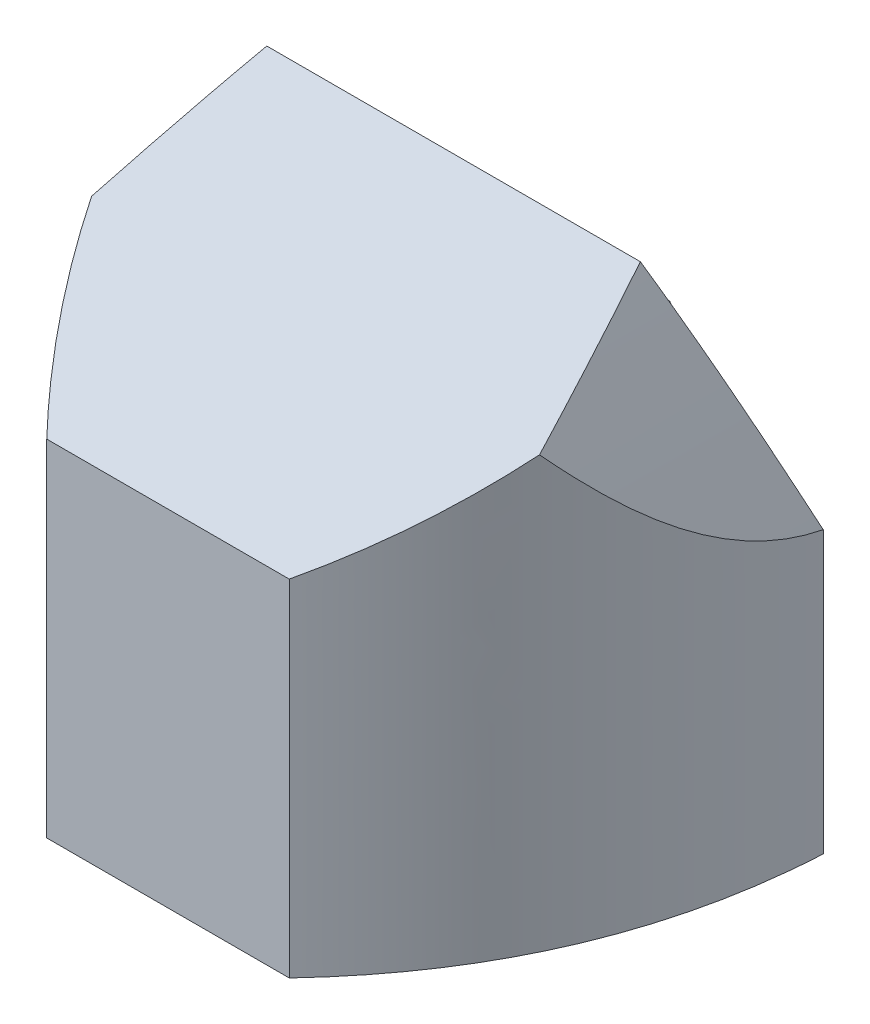
SolidWorks part; units mm, degrees
ref_plane "Front Plane" through (0, 0, 0) normal (0, 0, 1) x (1, 0, 0)
ref_plane "Top Plane" through (0, 0, 0) normal (0, 1, 0) x (1, 0, 0)
ref_plane "Right Plane" through (0, 0, 0) normal (1, 0, 0) x (0, 0, -1)
sketch "Sketch2" plane through (0, 0, 0) normal (1, 0, 0) x (0, 0, -1)
  line L0 (0, 0) -> (0, -750) construction
  line L1 (0, -750) -> (-500, -750)
  line L2 (-500, -750) -> (-500, -288.6751)
  line L3 (-500, -288.6751) -> (-118.677, -68.5182)
  line L4 (-118.677, -68.5182) -> (0, -375)
  line L5 (0, -750) -> (0, -375)
  dimension "D1" = 60
  dimension "D2" = 750
  dimension "D3" = 500
extrude "Boss-Extrude1" add sketch "Sketch2" along normal mid plane 1000
sketch "Sketch3" plane through (0, -750, 0) normal (0, -1, 0) x (1, 0, 0)
  line L2 (0, 500) -> (0, 0) construction
  line L4 (-161.9217, 500) -> (-500, 500)
  line L5 (-500, 500) -> (-500, 0)
  line L6 (-500, 0) -> (500, 0)
  line L7 (500, 0) -> (500, 500)
  line L8 (500, 500) -> (-500, 500)
  line L9 (-500, 500) -> (-500, 0)
  line L11 (500, 0) -> (500, 500)
  line L12 (500, 500) -> (161.9217, 500)
  line L13 (500, 500) -> (-500, 500) construction
  line L14 (500, 0) -> (-500, 0) construction
  line L16 (375, 0) -> (500, 0)
  line L17 (-500, 0) -> (-375, 0)
  spline S0 degree 2 poles (-375, 0) (-359.9342, 289.4316) (-161.9217, 500) knots 0 0 0 1 1 1
  spline S1 degree 2 poles (375, 0) (359.9342, 289.4316) (161.9217, 500) knots 0 0 0 1 1 1
  point P7 (-256.7752, 500)
  point P10 (-256.3318, 500)
  point P11 (-311.7603, 275.3697)
  point P14 (-161.9217, 500)
  dimension "D2" = 750
  dimension "D1" = 0
extrude "Cut-Extrude1" cut sketch "Sketch3" against normal blind 1000
sketch "Sketch4" plane through (0, 0, 0) normal (0, 0, -1) x (-1, 0, 0)
  line L0 (0, 174.7035) -> (0, -750) construction
  line L1 (-375, -750) -> (375, -750) construction
  line L3 (-375, -375) -> (-996.2943, -375)
  line L4 (-996.2943, -375) -> (-996.2943, 371.9099)
  line L5 (-996.2943, 371.9099) -> (846.4896, 371.9099)
  line L6 (846.4896, 371.9099) -> (846.4896, -375)
  line L7 (846.4896, -375) -> (375, -375)
  spline S0 degree 2 poles (-375, -375) (0, 724.4071) (375, -375) knots 0 0 0 1 1 1
extrude "Cut-Extrude2" cut sketch "Sketch4" against normal blind 1000
sketch "Sketch5" plane through (0, -48.8966, 126.2749) normal (0, 0.3611, -0.9325) x (-1, 0, 0)
  line L0 (-249.4412, -21.0413) -> (249.4412, -21.0413) construction
  line L1 (254, -289.5188) -> (-254, -289.5188)
  line L2 (254, -289.5188) -> (254, -86.3188)
  line L3 (254, -86.3188) -> (-254, -86.3188)
  line L4 (-254, -289.5188) -> (-254, -86.3188)
  line L5 (254, -289.5188) -> (-254, -86.3188) construction
  line L6 (254, -86.3188) -> (-254, -289.5188) construction
  line L7 (266.7, -73.6188) -> (-266.7, -73.6188)
  line L8 (-266.7, -302.2188) -> (-266.7, -73.6188)
  line L9 (266.7, -302.2188) -> (-266.7, -302.2188)
  line L10 (266.7, -302.2188) -> (266.7, -73.6188)
  point P0 (0, -187.9188)
  point P5 (-485.9279, -187.9188)
  point P7 (-493.477, -195.4678)
  point P8 (0, 0)
  point P10 (0, -21.0413)
  dimension "D1" = 203.2
  dimension "D2" = 508
  dimension "D3" = 12.7
extrude "Boss-Extrude2" add sketch "Sketch5" along normal blind 3.175
sketch "Sketch6" plane through (0, 0, 0) normal (0, 0, -1) x (-1, 0, 0)
  line L0 (-375, -750) -> (375, -750) construction
  line L1 (-254, -750) -> (-101.6, -750)
  line L2 (-254, -750) -> (-254, -375)
  line L3 (-254, -375) -> (-101.6, -375)
  line L4 (-101.6, -750) -> (-101.6, -375)
  line L5 (0, -750) -> (0, -624.6527) construction
  line L6 (-375, -375) -> (375, -375) construction
  line L7 (254, -750) -> (101.6, -750)
  line L8 (101.6, -750) -> (101.6, -375)
  line L9 (254, -375) -> (101.6, -375)
  line L10 (254, -750) -> (254, -375)
  point P8 (-754.4075, -441.2771)
  point P9 (-589.4664, -422.8425)
  dimension "D1" = 152.4
  dimension "D2" = 101.6
extrude "Cut-Extrude4" cut sketch "Sketch6" against normal blind 381
sketch "Sketch7" plane through (0, 0, 0) normal (1, 0, 0) x (0, 0, -1)
  line L0 (0, -375) -> (152.4, -566.8042)
  line L1 (152.4, -566.8042) -> (152.4, -750)
  line L2 (152.4, -750) -> (0, -750)
  line L3 (0, -375) -> (0, -750)
  dimension "D1" = 152.4
extrude "Boss-Extrude4" add sketch "Sketch7" along normal mid plane 152.4
